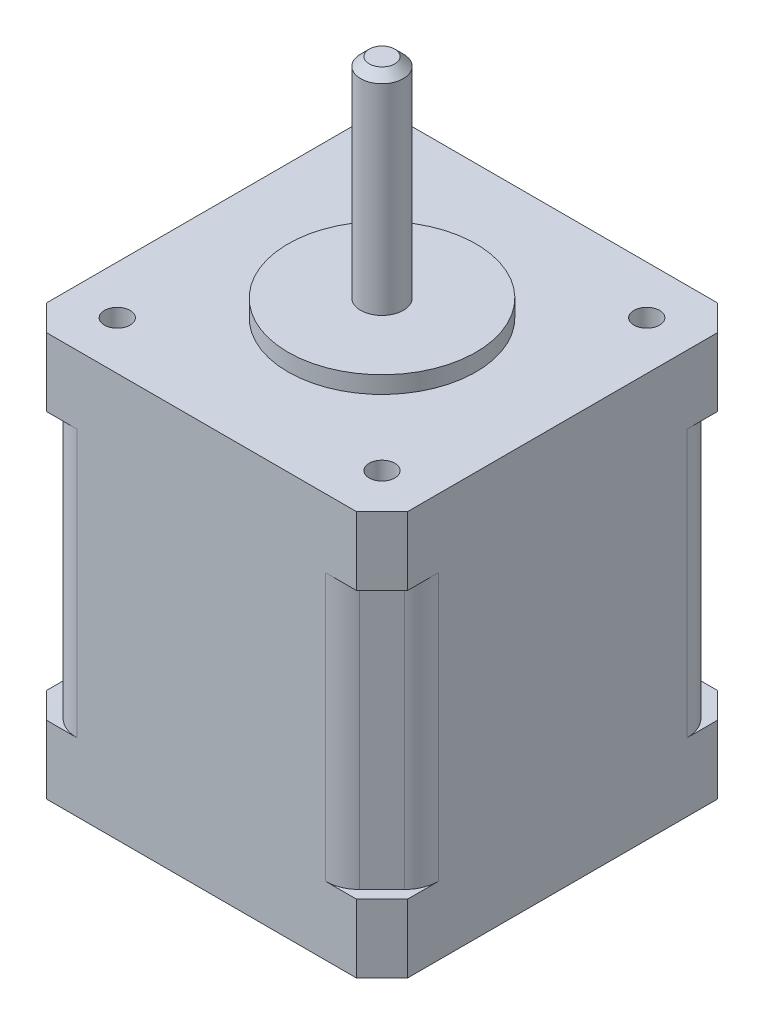
SolidWorks part; units mm, degrees
ref_plane "Plan de face" through (0, 0, 0) normal (0, 0, 1) x (1, 0, 0)
ref_plane "Plan de dessus" through (0, 0, 0) normal (0, 1, 0) x (1, 0, 0)
ref_plane "Plan de droite" through (0, 0, 0) normal (1, 0, 0) x (0, 0, -1)
sketch "Esquisse1" plane through (0, 0, 0) normal (0, 1, 0) x (1, 0, 0)
  line L0 (-15.8475, 14.7034) -> (26.4525, -27.5966) construction
  line L1 (-15.8475, 14.7034) -> (26.4525, 14.7034)
  line L2 (-15.8475, 14.7034) -> (-15.8475, -27.5966)
  line L3 (-15.8475, -27.5966) -> (26.4525, -27.5966)
  line L4 (26.4525, 14.7034) -> (26.4525, -27.5966)
  line L5 (-15.8475, -27.5966) -> (26.4525, 14.7034) construction
  line L6 (-10.1975, 9.0534) -> (20.8025, 9.0534) construction
  line L7 (-10.1975, 9.0534) -> (-10.1975, -21.9466) construction
  line L8 (20.8025, 9.0534) -> (20.8025, -21.9466) construction
  circle A0 centre (5.3025, -6.4466) radius 2.5
  circle A1 centre (-10.1975, 9.0534) radius 1.5
  circle A2 centre (20.8025, 9.0534) radius 1.5
  circle A3 centre (20.8025, -21.9466) radius 1.5
  circle A4 centre (-10.1975, -21.9466) radius 1.5
  dimension "D3" = 5
  dimension "D4" = 3
  dimension "D5" = 31
  dimension "D2" = 42.3
extrude "Boss.-Extru.1" add sketch "Esquisse1" along normal blind 47.3
sketch "Esquisse2" plane through (0, 47.3, 0) normal (0, 1, 0) x (1, 0, 0)
  circle A0 centre (5.3025, -6.4466) radius 11
  dimension "D1" = 22
extrude "Boss.-Extru.2" add sketch "Esquisse2" along normal blind 2
sketch "Esquisse3" plane through (0, 49.3, 0) normal (0, 1, 0) x (1, 0, 0)
  circle A0 centre (5.3025, -6.4466) radius 2.5
  circle A2 centre (5.3025, -6.4466) radius 11 construction
  dimension "D1" = 5
extrude "Boss.-Extru.3" add sketch "Esquisse3" along normal blind 24.5
chamfer "Chanfrein1" distance 1 angle 45 1 edges at (5.3025, 73.8, 8.9466)
ref_plane "Plan1" through (0, 0, 6.4466) normal (0, 0, -1) x (-1, 0, 0)
sketch "Esquisse4" plane through (0, 47.3, 0) normal (0, 1, 0) x (1, 0, 0)
  line L0 (-14.6759, -23.8184) -> (-12.0693, -26.425)
  line L1 (-15.8475, 14.7034) -> (-15.8475, -27.5966) construction
  line L2 (-15.8475, -27.5966) -> (26.4525, -27.5966) construction
  line L3 (-9.2409, -27.5966) -> (19.8459, -27.5966)
  line L4 (22.6744, -26.425) -> (25.281, -23.8184)
  line L5 (26.4525, -27.5966) -> (26.4525, 14.7034) construction
  line L6 (26.4525, -20.99) -> (26.4525, 8.0968)
  line L7 (25.281, 10.9252) -> (22.6744, 13.5318)
  line L8 (26.4525, 14.7034) -> (-15.8475, 14.7034) construction
  line L9 (19.8459, 14.7034) -> (-9.2409, 14.7034)
  line L10 (-12.0693, 13.5318) -> (-14.6759, 10.9252)
  line L11 (-15.8475, 8.0968) -> (-15.8475, -20.99)
  arc A0 (19.8459, -27.5966) -> (22.6744, -26.425) centre (19.8459, -23.5966) ccw
  arc A1 (25.281, -23.8184) -> (26.4525, -20.99) centre (22.4525, -20.99) ccw
  arc A2 (26.4525, 8.0968) -> (25.281, 10.9252) centre (22.4525, 8.0968) ccw
  arc A3 (22.6744, 13.5318) -> (19.8459, 14.7034) centre (19.8459, 10.7034) ccw
  arc A4 (-9.2409, 14.7034) -> (-12.0693, 13.5318) centre (-9.2409, 10.7034) ccw
  arc A5 (-14.6759, 10.9252) -> (-15.8475, 8.0968) centre (-11.8475, 8.0968) ccw
  arc A6 (-12.0693, -26.425) -> (-9.2409, -27.5966) centre (-9.2409, -23.5966) ccw
  arc A7 (-14.6759, -23.8184) -> (-15.8475, -20.99) centre (-11.8475, -20.99) cw
  point P18 (21.5028, -27.5966)
  point P21 (26.4525, -22.6469)
  point P24 (26.4525, 9.7536)
  point P27 (21.5028, 14.7034)
  point P30 (-10.8977, 14.7034)
  point P33 (-15.8475, 9.7536)
  point P36 (-10.8977, -27.5966)
  point P39 (-15.8475, -22.6469)
  dimension "D6" = 4
  dimension "D1" = 7
  dimension "D2" = 7
  dimension "D3" = 7
  dimension "D4" = 7
  dimension "D5" = 45
extrude "Enlèv. mat.-Extru.1" cut sketch "Esquisse4" against normal offset from surface (31.3 mm away) 8 from offset 8 flip side to cut up to face at (5.3025, 0, 6.4466) offset against normal yes
chamfer "Chanfrein2" distance 3 angle 45 8 edges at (-15.8475, 4, -14.7034) (-15.8475, 43.3, -14.7034) (26.4525, 4, -14.7034) (26.4525, 43.3, -14.7034) (-15.8475, 4, 27.5966) (-15.8475, 43.3, 27.5966) (26.4525, 4, 27.5966) (26.4525, 43.3, 27.5966)
sketch "Esquisse5" plane through (0, 0, 0) normal (0, -1, 0) x (1, 0, 0)
  circle A0 centre (-10.1975, -9.0534) radius 3
  circle A1 centre (-10.1975, 21.9466) radius 3
  circle A2 centre (20.8025, 21.9466) radius 3
  circle A3 centre (20.8025, -9.0534) radius 3
  dimension "D1" = 6
  dimension "D2" = 6
  dimension "D3" = 6
  dimension "D4" = 6
extrude "Enlèv. mat.-Extru.2" cut sketch "Esquisse5" against normal blind 2
sketch "Esquisse6" plane through (0, 0, -14.7034) normal (0, 0, -1) x (-1, 0, 0)
  line L0 (-9.3025, 0) -> (-1.3025, 0)
  line L1 (-9.3025, 0) -> (-9.3025, 4)
  line L2 (-1.3025, 0) -> (-1.3025, 4)
  line L3 (-9.3025, 4) -> (-1.3025, 4)
  line L4 (-23.4525, 0) -> (12.8475, 0) construction
  line L5 (-5.3025, 47.3) -> (-5.3025, 0) construction
  line L6 (-23.4525, 47.3) -> (12.8475, 47.3) construction
  dimension "D1" = 4
  dimension "D2" = 8
extrude "Boss.-Extru.4" add sketch "Esquisse6" along normal blind 2
sketch "Esquisse7" plane through (0, 0, -16.7034) normal (0, 0, -1) x (-1, 0, 0)
  line L0 (-9.3025, 2) -> (-1.3025, 2) construction
  line L1 (-9.3025, 4) -> (-9.3025, 0) construction
  line L2 (-1.3025, 0) -> (-1.3025, 4) construction
  circle A0 centre (-7.5525, 2) radius 1
  circle A1 centre (-6.0525, 2) radius 1
  circle A2 centre (-4.5525, 2) radius 1
  circle A3 centre (-3.0525, 2) radius 1
  dimension "D1" = 2
  dimension "D2" = 1.5
  dimension "D3" = 1.5
  dimension "D4" = 1.5
  dimension "D5" = 1.75
extrude "Boss.-Extru.6" add sketch "Esquisse7" along normal blind 2 contours A0 L0 A1 | L0 A0 A1 | A0 L0 A2 A1 | L0 A0 A1 A2 | A1 L0 A3 A2 | L0 A1 A2 A3 | A2 L0 A3 | L0 A2 A3 | L0 A3 A2 | A3 L0 A2 | A2 L0 A1 | L0 A2 A1 | A1 L0 A0 | L0 A1 A0
